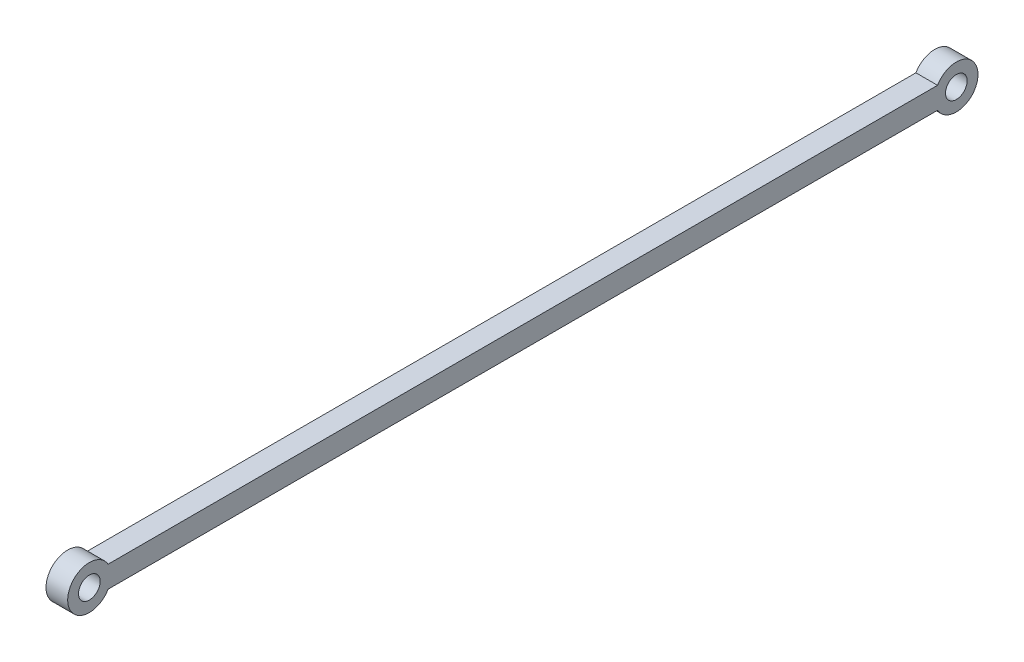
SolidWorks part; units mm, degrees
ref_plane "정면" through (0, 0, 0) normal (0, 0, 1) x (1, 0, 0)
ref_plane "윗면" through (0, 0, 0) normal (0, 1, 0) x (1, 0, 0)
ref_plane "우측면" through (0, 0, 0) normal (1, 0, 0) x (0, 0, -1)
sketch "스케치1" plane through (0, 0, 0) normal (1, 0, 0) x (0, 0, -1)
  line L0 (-50, 0) -> (50, 0) construction
  line L1 (-47.8349, 1.25) -> (47.8349, 1.25)
  line L3 (-47.8349, -1.25) -> (47.8349, -1.25)
  line L5 (0, 1.25) -> (0, -1.25) construction
  arc A0 (-47.8349, 1.25) -> (-47.8349, -1.25) centre (-50, 0) ccw
  circle A1 centre (-50, 0) radius 1.25
  arc A2 (47.8349, -1.25) -> (47.8349, 1.25) centre (50, 0) ccw
  circle A3 centre (50, 0) radius 1.25
  dimension "D3" = 5
  dimension "D4" = 5
  dimension "D1" = 2.5
  dimension "D2" = 100
extrude "보스-돌출1" add sketch "스케치1" along normal blind 2.5
equation "\"link11\" = 80"
equation "\"link12\" = 40"
equation "\"link21\"= 60"
equation "\"link22\"= 40"
equation "\"link31\"= 50"
equation "\"link32\"= 40"
equation "\"link41\"= 40"
equation "\"link42\"= 40"
